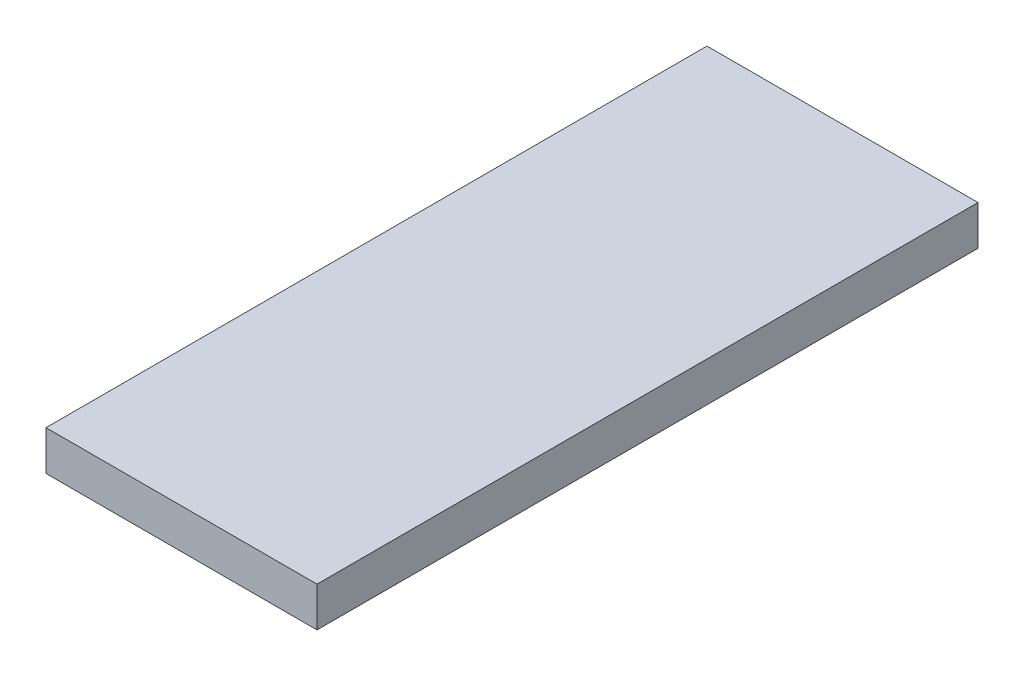
SolidWorks part; units mm, degrees
material "Manual Density from Real Component Bordo attacco e uscita"
ref_plane "Piano frontale" through (0, 0, 0) normal (0, 0, 1) x (1, 0, 0)
ref_plane "Piano superiore" through (0, 0, 0) normal (0, 1, 0) x (1, 0, 0)
ref_plane "Piano destro" through (0, 0, 0) normal (1, 0, 0) x (0, 0, -1)
sketch "Schizzo1" plane through (0, 0, 0) normal (0, 0, 1) x (1, 0, 0)
  line L1 (4.1, -0.6) -> (-4.1, -0.6)
  line L2 (4.1, -0.6) -> (4.1, 0.6)
  line L3 (4.1, 0.6) -> (-4.1, 0.6)
  line L4 (-4.1, -0.6) -> (-4.1, 0.6)
  line L5 (4.1, -0.6) -> (-4.1, 0.6) construction
  line L6 (4.1, 0.6) -> (-4.1, -0.6) construction
  point P0 (0, 0)
  dimension "D1" = 1.2
  dimension "D2" = 8.2
extrude "Estrusione-Estrusione1" add sketch "Schizzo1" along normal blind 20
